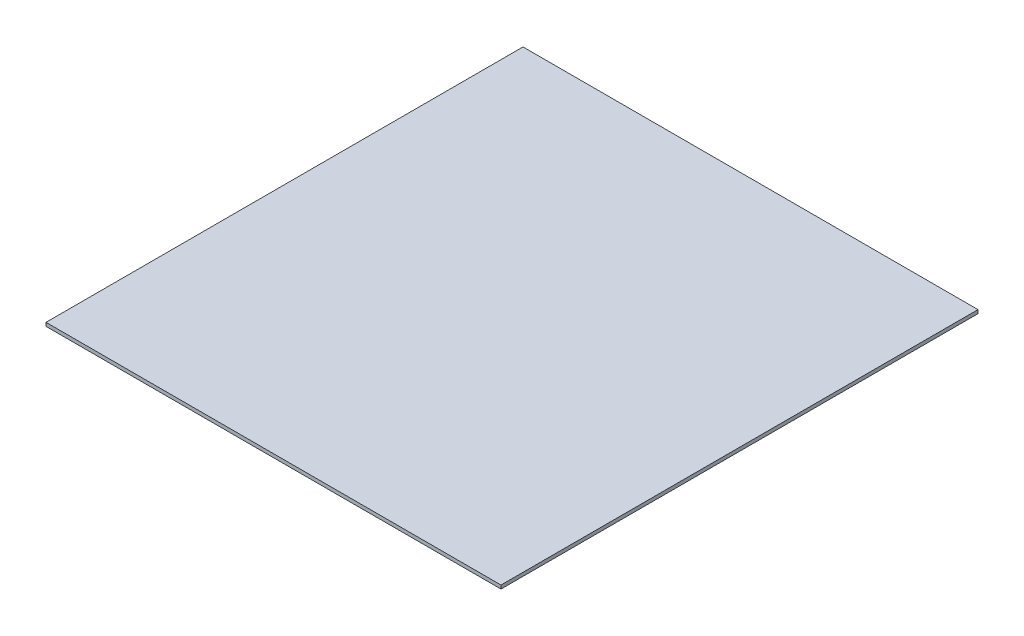
SolidWorks part; units mm, degrees
ref_plane "Front Plane" through (0, 0, 0) normal (0, 0, 1) x (1, 0, 0)
ref_plane "Top Plane" through (0, 0, 0) normal (0, 1, 0) x (1, 0, 0)
ref_plane "Right Plane" through (0, 0, 0) normal (1, 0, 0) x (0, 0, -1)
sketch "Sketch2" plane through (0, 0, 0) normal (0, 1, 0) x (1, 0, 0)
  line L1 (-98.425, 103.1875) -> (98.425, 103.1875)
  line L2 (-98.425, 103.1875) -> (-98.425, -103.1875)
  line L3 (-98.425, -103.1875) -> (98.425, -103.1875)
  line L4 (98.425, 103.1875) -> (98.425, -103.1875)
  line L5 (-98.425, 103.1875) -> (98.425, -103.1875) construction
  line L6 (-98.425, -103.1875) -> (98.425, 103.1875) construction
  point P0 (0, 0)
  dimension "D1" = 196.85
  dimension "D2" = 206.375
extrude "Boss-Extrude1" add sketch "Sketch2" along normal blind 1.524
